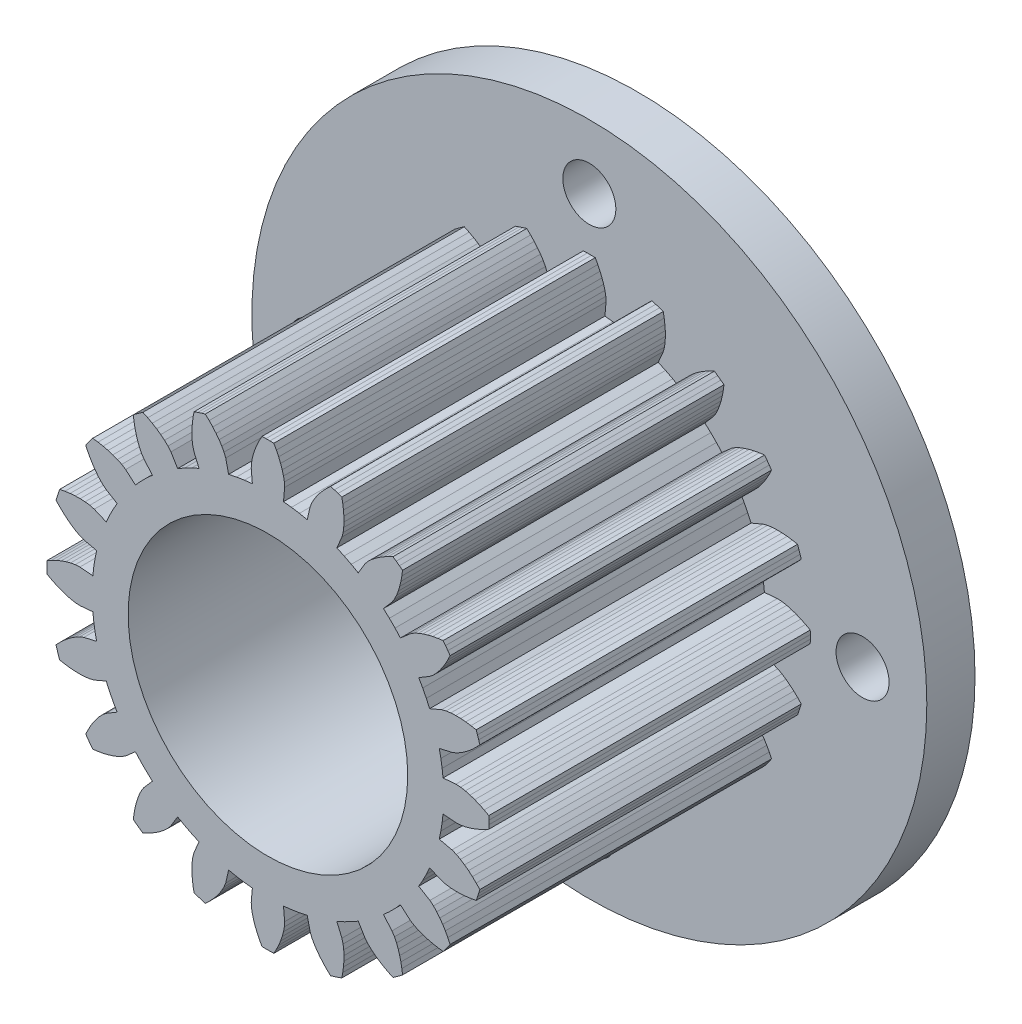
SolidWorks part; units mm, degrees
ref_plane "Спереди" through (0, 0, 0) normal (0, 0, 1) x (1, 0, 0)
ref_plane "Сверху" through (0, 0, 0) normal (0, 1, 0) x (1, 0, 0)
ref_plane "Справа" through (0, 0, 0) normal (1, 0, 0) x (0, 0, -1)
sketch "Эскиз1" plane through (0, 0, 0) normal (0, 0, 1) x (1, 0, 0)
  line L0 (10.8946, -0.9683) -> (11.7, -1.0399)
  line L1 (11.7, -1.0399) -> (11.9889, -1.0227)
  line L2 (11.9889, -1.0227) -> (12.2805, -0.9687)
  line L3 (12.2805, -0.9687) -> (12.5736, -0.889)
  line L4 (12.5736, -0.889) -> (12.8671, -0.7875)
  line L5 (12.8671, -0.7875) -> (13.1606, -0.6661)
  line L6 (13.1606, -0.6661) -> (13.4535, -0.5261)
  line L7 (13.4535, -0.5261) -> (13.7451, -0.3683)
  line L8 (13.7451, -0.3683) -> (13.7495, -0.1228)
  line L9 (13.7495, -0.1228) -> (13.7495, 0.1228)
  line L10 (13.7495, 0.1228) -> (13.7451, 0.3683)
  line L11 (13.7451, 0.3683) -> (13.4535, 0.5261)
  line L12 (13.4535, 0.5261) -> (13.1606, 0.6661)
  line L13 (13.1606, 0.6661) -> (12.8671, 0.7875)
  line L14 (12.8671, 0.7875) -> (12.5736, 0.889)
  line L15 (12.5736, 0.889) -> (12.2805, 0.9687)
  line L16 (12.2805, 0.9687) -> (11.9889, 1.0227)
  line L17 (11.9889, 1.0227) -> (11.7, 1.0399)
  line L18 (11.7, 1.0399) -> (10.8946, 0.9683)
  line L19 (10.8946, 0.9683) -> (10.8391, 1.4641)
  line L20 (10.8391, 1.4641) -> (10.761, 1.957)
  line L21 (10.761, 1.957) -> (10.6606, 2.4457)
  line L22 (10.6606, 2.4457) -> (11.4487, 2.6265)
  line L23 (11.4487, 2.6265) -> (11.7181, 2.7321)
  line L24 (11.7181, 2.7321) -> (11.9788, 2.8737)
  line L25 (11.9788, 2.8737) -> (12.2329, 3.0399)
  line L26 (12.2329, 3.0399) -> (12.4807, 3.2272)
  line L27 (12.4807, 3.2272) -> (12.7223, 3.4333)
  line L28 (12.7223, 3.4333) -> (12.9576, 3.657)
  line L29 (12.9576, 3.657) -> (13.1861, 3.8972)
  line L30 (13.1861, 3.8972) -> (13.1144, 4.1321)
  line L31 (13.1144, 4.1321) -> (13.0386, 4.3656)
  line L32 (13.0386, 4.3656) -> (12.9585, 4.5977)
  line L33 (12.9585, 4.5977) -> (12.6324, 4.6577)
  line L34 (12.6324, 4.6577) -> (12.3107, 4.7004)
  line L35 (12.3107, 4.7004) -> (11.994, 4.7252)
  line L36 (11.994, 4.7252) -> (11.6834, 4.731)
  line L37 (11.6834, 4.731) -> (11.3802, 4.7161)
  line L38 (11.3802, 4.7161) -> (11.0861, 4.6774)
  line L39 (11.0861, 4.6774) -> (10.8061, 4.6045)
  line L40 (10.8061, 4.6045) -> (10.0621, 4.2875)
  line L41 (10.0621, 4.2875) -> (9.8561, 4.7419)
  line L42 (9.8561, 4.7419) -> (9.6296, 5.1865)
  line L43 (9.6296, 5.1865) -> (9.383, 5.6203)
  line L44 (9.383, 5.6203) -> (10.0767, 6.0358)
  line L45 (10.0767, 6.0358) -> (10.3003, 6.2195)
  line L46 (10.3003, 6.2195) -> (10.5045, 6.4347)
  line L47 (10.5045, 6.4347) -> (10.6948, 6.6713)
  line L48 (10.6948, 6.6713) -> (10.8726, 6.926)
  line L49 (10.8726, 6.926) -> (11.0387, 7.1967)
  line L50 (11.0387, 7.1967) -> (11.1933, 7.4821)
  line L51 (11.1933, 7.4821) -> (11.3364, 7.7812)
  line L52 (11.3364, 7.7812) -> (11.1957, 7.9824)
  line L53 (11.1957, 7.9824) -> (11.0514, 8.181)
  line L54 (11.0514, 8.181) -> (10.9035, 8.3771)
  line L55 (10.9035, 8.3771) -> (10.5749, 8.3333)
  line L56 (10.5749, 8.3333) -> (10.2556, 8.2745)
  line L57 (10.2556, 8.2745) -> (9.9468, 8.2002)
  line L58 (9.9468, 8.2002) -> (9.6497, 8.1098)
  line L59 (9.6497, 8.1098) -> (9.3658, 8.002)
  line L60 (9.3658, 8.002) -> (9.0981, 7.8742)
  line L61 (9.0981, 7.8742) -> (8.8543, 7.7184)
  line L62 (8.8543, 7.7184) -> (8.2447, 7.187)
  line L63 (8.2447, 7.187) -> (7.9084, 7.5556)
  line L64 (7.9084, 7.5556) -> (7.5556, 7.9084)
  line L65 (7.5556, 7.9084) -> (7.187, 8.2447)
  line L66 (7.187, 8.2447) -> (7.7184, 8.8543)
  line L67 (7.7184, 8.8543) -> (7.8742, 9.0981)
  line L68 (7.8742, 9.0981) -> (8.002, 9.3658)
  line L69 (8.002, 9.3658) -> (8.1098, 9.6497)
  line L70 (8.1098, 9.6497) -> (8.2002, 9.9468)
  line L71 (8.2002, 9.9468) -> (8.2745, 10.2556)
  line L72 (8.2745, 10.2556) -> (8.3333, 10.5749)
  line L73 (8.3333, 10.5749) -> (8.3771, 10.9035)
  line L74 (8.3771, 10.9035) -> (8.181, 11.0514)
  line L75 (8.181, 11.0514) -> (7.9824, 11.1957)
  line L76 (7.9824, 11.1957) -> (7.7812, 11.3364)
  line L77 (7.7812, 11.3364) -> (7.4821, 11.1933)
  line L78 (7.4821, 11.1933) -> (7.1967, 11.0387)
  line L79 (7.1967, 11.0387) -> (6.926, 10.8726)
  line L80 (6.926, 10.8726) -> (6.6713, 10.6948)
  line L81 (6.6713, 10.6948) -> (6.4347, 10.5045)
  line L82 (6.4347, 10.5045) -> (6.2195, 10.3003)
  line L83 (6.2195, 10.3003) -> (6.0358, 10.0767)
  line L84 (6.0358, 10.0767) -> (5.6203, 9.383)
  line L85 (5.6203, 9.383) -> (5.1865, 9.6296)
  line L86 (5.1865, 9.6296) -> (4.7419, 9.8561)
  line L87 (4.7419, 9.8561) -> (4.2875, 10.0621)
  line L88 (4.2875, 10.0621) -> (4.6045, 10.8061)
  line L89 (4.6045, 10.8061) -> (4.6774, 11.0861)
  line L90 (4.6774, 11.0861) -> (4.7161, 11.3802)
  line L91 (4.7161, 11.3802) -> (4.731, 11.6834)
  line L92 (4.731, 11.6834) -> (4.7252, 11.994)
  line L93 (4.7252, 11.994) -> (4.7004, 12.3107)
  line L94 (4.7004, 12.3107) -> (4.6577, 12.6324)
  line L95 (4.6577, 12.6324) -> (4.5977, 12.9585)
  line L96 (4.5977, 12.9585) -> (4.3656, 13.0386)
  line L97 (4.3656, 13.0386) -> (4.1321, 13.1144)
  line L98 (4.1321, 13.1144) -> (3.8972, 13.1861)
  line L99 (3.8972, 13.1861) -> (3.657, 12.9576)
  line L100 (3.657, 12.9576) -> (3.4333, 12.7223)
  line L101 (3.4333, 12.7223) -> (3.2272, 12.4807)
  line L102 (3.2272, 12.4807) -> (3.0399, 12.2329)
  line L103 (3.0399, 12.2329) -> (2.8737, 11.9788)
  line L104 (2.8737, 11.9788) -> (2.7321, 11.7181)
  line L105 (2.7321, 11.7181) -> (2.6265, 11.4487)
  line L106 (2.6265, 11.4487) -> (2.4457, 10.6606)
  line L107 (2.4457, 10.6606) -> (1.957, 10.761)
  line L108 (1.957, 10.761) -> (1.4641, 10.8391)
  line L109 (1.4641, 10.8391) -> (0.9683, 10.8946)
  line L110 (0.9683, 10.8946) -> (1.0399, 11.7)
  line L111 (1.0399, 11.7) -> (1.0227, 11.9889)
  line L112 (1.0227, 11.9889) -> (0.9687, 12.2805)
  line L113 (0.9687, 12.2805) -> (0.889, 12.5736)
  line L114 (0.889, 12.5736) -> (0.7875, 12.8671)
  line L115 (0.7875, 12.8671) -> (0.6661, 13.1606)
  line L116 (0.6661, 13.1606) -> (0.5261, 13.4535)
  line L117 (0.5261, 13.4535) -> (0.3683, 13.7451)
  line L118 (0.3683, 13.7451) -> (0.1228, 13.7495)
  line L119 (0.1228, 13.7495) -> (-0.1228, 13.7495)
  line L120 (-0.1228, 13.7495) -> (-0.3683, 13.7451)
  line L121 (-0.3683, 13.7451) -> (-0.5261, 13.4535)
  line L122 (-0.5261, 13.4535) -> (-0.6661, 13.1606)
  line L123 (-0.6661, 13.1606) -> (-0.7875, 12.8671)
  line L124 (-0.7875, 12.8671) -> (-0.889, 12.5736)
  line L125 (-0.889, 12.5736) -> (-0.9687, 12.2805)
  line L126 (-0.9687, 12.2805) -> (-1.0227, 11.9889)
  line L127 (-1.0227, 11.9889) -> (-1.0399, 11.7)
  line L128 (-1.0399, 11.7) -> (-0.9683, 10.8946)
  line L129 (-0.9683, 10.8946) -> (-1.4641, 10.8391)
  line L130 (-1.4641, 10.8391) -> (-1.957, 10.761)
  line L131 (-1.957, 10.761) -> (-2.4457, 10.6606)
  line L132 (-2.4457, 10.6606) -> (-2.6265, 11.4487)
  line L133 (-2.6265, 11.4487) -> (-2.7321, 11.7181)
  line L134 (-2.7321, 11.7181) -> (-2.8737, 11.9788)
  line L135 (-2.8737, 11.9788) -> (-3.0399, 12.2329)
  line L136 (-3.0399, 12.2329) -> (-3.2272, 12.4807)
  line L137 (-3.2272, 12.4807) -> (-3.4333, 12.7223)
  line L138 (-3.4333, 12.7223) -> (-3.657, 12.9576)
  line L139 (-3.657, 12.9576) -> (-3.8972, 13.1861)
  line L140 (-3.8972, 13.1861) -> (-4.1321, 13.1144)
  line L141 (-4.1321, 13.1144) -> (-4.3656, 13.0386)
  line L142 (-4.3656, 13.0386) -> (-4.5977, 12.9585)
  line L143 (-4.5977, 12.9585) -> (-4.6577, 12.6324)
  line L144 (-4.6577, 12.6324) -> (-4.7004, 12.3107)
  line L145 (-4.7004, 12.3107) -> (-4.7252, 11.994)
  line L146 (-4.7252, 11.994) -> (-4.731, 11.6834)
  line L147 (-4.731, 11.6834) -> (-4.7161, 11.3802)
  line L148 (-4.7161, 11.3802) -> (-4.6774, 11.0861)
  line L149 (-4.6774, 11.0861) -> (-4.6045, 10.8061)
  line L150 (-4.6045, 10.8061) -> (-4.2875, 10.0621)
  line L151 (-4.2875, 10.0621) -> (-4.7419, 9.8561)
  line L152 (-4.7419, 9.8561) -> (-5.1865, 9.6296)
  line L153 (-5.1865, 9.6296) -> (-5.6203, 9.383)
  line L154 (-5.6203, 9.383) -> (-6.0358, 10.0767)
  line L155 (-6.0358, 10.0767) -> (-6.2195, 10.3003)
  line L156 (-6.2195, 10.3003) -> (-6.4347, 10.5045)
  line L157 (-6.4347, 10.5045) -> (-6.6713, 10.6948)
  line L158 (-6.6713, 10.6948) -> (-6.926, 10.8726)
  line L159 (-6.926, 10.8726) -> (-7.1967, 11.0387)
  line L160 (-7.1967, 11.0387) -> (-7.4821, 11.1933)
  line L161 (-7.4821, 11.1933) -> (-7.7812, 11.3364)
  line L162 (-7.7812, 11.3364) -> (-7.9824, 11.1957)
  line L163 (-7.9824, 11.1957) -> (-8.181, 11.0514)
  line L164 (-8.181, 11.0514) -> (-8.3771, 10.9035)
  line L165 (-8.3771, 10.9035) -> (-8.3333, 10.5749)
  line L166 (-8.3333, 10.5749) -> (-8.2745, 10.2556)
  line L167 (-8.2745, 10.2556) -> (-8.2002, 9.9468)
  line L168 (-8.2002, 9.9468) -> (-8.1098, 9.6497)
  line L169 (-8.1098, 9.6497) -> (-8.002, 9.3658)
  line L170 (-8.002, 9.3658) -> (-7.8742, 9.0981)
  line L171 (-7.8742, 9.0981) -> (-7.7184, 8.8543)
  line L172 (-7.7184, 8.8543) -> (-7.187, 8.2447)
  line L173 (-7.187, 8.2447) -> (-7.5556, 7.9084)
  line L174 (-7.5556, 7.9084) -> (-7.9084, 7.5556)
  line L175 (-7.9084, 7.5556) -> (-8.2447, 7.187)
  line L176 (-8.2447, 7.187) -> (-8.8543, 7.7184)
  line L177 (-8.8543, 7.7184) -> (-9.0981, 7.8742)
  line L178 (-9.0981, 7.8742) -> (-9.3658, 8.002)
  line L179 (-9.3658, 8.002) -> (-9.6497, 8.1098)
  line L180 (-9.6497, 8.1098) -> (-9.9468, 8.2002)
  line L181 (-9.9468, 8.2002) -> (-10.2556, 8.2745)
  line L182 (-10.2556, 8.2745) -> (-10.5749, 8.3333)
  line L183 (-10.5749, 8.3333) -> (-10.9035, 8.3771)
  line L184 (-10.9035, 8.3771) -> (-11.0514, 8.181)
  line L185 (-11.0514, 8.181) -> (-11.1957, 7.9824)
  line L186 (-11.1957, 7.9824) -> (-11.3364, 7.7812)
  line L187 (-11.3364, 7.7812) -> (-11.1933, 7.4821)
  line L188 (-11.1933, 7.4821) -> (-11.0387, 7.1967)
  line L189 (-11.0387, 7.1967) -> (-10.8726, 6.926)
  line L190 (-10.8726, 6.926) -> (-10.6948, 6.6713)
  line L191 (-10.6948, 6.6713) -> (-10.5045, 6.4347)
  line L192 (-10.5045, 6.4347) -> (-10.3003, 6.2195)
  line L193 (-10.3003, 6.2195) -> (-10.0767, 6.0358)
  line L194 (-10.0767, 6.0358) -> (-9.383, 5.6203)
  line L195 (-9.383, 5.6203) -> (-9.6296, 5.1865)
  line L196 (-9.6296, 5.1865) -> (-9.8561, 4.7419)
  line L197 (-9.8561, 4.7419) -> (-10.0621, 4.2875)
  line L198 (-10.0621, 4.2875) -> (-10.8061, 4.6045)
  line L199 (-10.8061, 4.6045) -> (-11.0861, 4.6774)
  line L200 (-11.0861, 4.6774) -> (-11.3802, 4.7161)
  line L201 (-11.3802, 4.7161) -> (-11.6834, 4.731)
  line L202 (-11.6834, 4.731) -> (-11.994, 4.7252)
  line L203 (-11.994, 4.7252) -> (-12.3107, 4.7004)
  line L204 (-12.3107, 4.7004) -> (-12.6324, 4.6577)
  line L205 (-12.6324, 4.6577) -> (-12.9585, 4.5977)
  line L206 (-12.9585, 4.5977) -> (-13.0386, 4.3656)
  line L207 (-13.0386, 4.3656) -> (-13.1144, 4.1321)
  line L208 (-13.1144, 4.1321) -> (-13.1861, 3.8972)
  line L209 (-13.1861, 3.8972) -> (-12.9576, 3.657)
  line L210 (-12.9576, 3.657) -> (-12.7223, 3.4333)
  line L211 (-12.7223, 3.4333) -> (-12.4807, 3.2272)
  line L212 (-12.4807, 3.2272) -> (-12.2329, 3.0399)
  line L213 (-12.2329, 3.0399) -> (-11.9788, 2.8737)
  line L214 (-11.9788, 2.8737) -> (-11.7181, 2.7321)
  line L215 (-11.7181, 2.7321) -> (-11.4487, 2.6265)
  line L216 (-11.4487, 2.6265) -> (-10.6606, 2.4457)
  line L217 (-10.6606, 2.4457) -> (-10.761, 1.957)
  line L218 (-10.761, 1.957) -> (-10.8391, 1.4641)
  line L219 (-10.8391, 1.4641) -> (-10.8946, 0.9683)
  line L220 (-10.8946, 0.9683) -> (-11.7, 1.0399)
  line L221 (-11.7, 1.0399) -> (-11.9889, 1.0227)
  line L222 (-11.9889, 1.0227) -> (-12.2805, 0.9687)
  line L223 (-12.2805, 0.9687) -> (-12.5736, 0.889)
  line L224 (-12.5736, 0.889) -> (-12.8671, 0.7875)
  line L225 (-12.8671, 0.7875) -> (-13.1606, 0.6661)
  line L226 (-13.1606, 0.6661) -> (-13.4535, 0.5261)
  line L227 (-13.4535, 0.5261) -> (-13.7451, 0.3683)
  line L228 (-13.7451, 0.3683) -> (-13.7495, 0.1228)
  line L229 (-13.7495, 0.1228) -> (-13.7495, -0.1228)
  line L230 (-13.7495, -0.1228) -> (-13.7451, -0.3683)
  line L231 (-13.7451, -0.3683) -> (-13.4535, -0.5261)
  line L232 (-13.4535, -0.5261) -> (-13.1606, -0.6661)
  line L233 (-13.1606, -0.6661) -> (-12.8671, -0.7875)
  line L234 (-12.8671, -0.7875) -> (-12.5736, -0.889)
  line L235 (-12.5736, -0.889) -> (-12.2805, -0.9687)
  line L236 (-12.2805, -0.9687) -> (-11.9889, -1.0227)
  line L237 (-11.9889, -1.0227) -> (-11.7, -1.0399)
  line L238 (-11.7, -1.0399) -> (-10.8946, -0.9683)
  line L239 (-10.8946, -0.9683) -> (-10.8391, -1.4641)
  line L240 (-10.8391, -1.4641) -> (-10.761, -1.957)
  line L241 (-10.761, -1.957) -> (-10.6606, -2.4457)
  line L242 (-10.6606, -2.4457) -> (-11.4487, -2.6265)
  line L243 (-11.4487, -2.6265) -> (-11.7181, -2.7321)
  line L244 (-11.7181, -2.7321) -> (-11.9788, -2.8737)
  line L245 (-11.9788, -2.8737) -> (-12.2329, -3.0399)
  line L246 (-12.2329, -3.0399) -> (-12.4807, -3.2272)
  line L247 (-12.4807, -3.2272) -> (-12.7223, -3.4333)
  line L248 (-12.7223, -3.4333) -> (-12.9576, -3.657)
  line L249 (-12.9576, -3.657) -> (-13.1861, -3.8972)
  line L250 (-13.1861, -3.8972) -> (-13.1144, -4.1321)
  line L251 (-13.1144, -4.1321) -> (-13.0386, -4.3656)
  line L252 (-13.0386, -4.3656) -> (-12.9585, -4.5977)
  line L253 (-12.9585, -4.5977) -> (-12.6324, -4.6577)
  line L254 (-12.6324, -4.6577) -> (-12.3107, -4.7004)
  line L255 (-12.3107, -4.7004) -> (-11.994, -4.7252)
  line L256 (-11.994, -4.7252) -> (-11.6834, -4.731)
  line L257 (-11.6834, -4.731) -> (-11.3802, -4.7161)
  line L258 (-11.3802, -4.7161) -> (-11.0861, -4.6774)
  line L259 (-11.0861, -4.6774) -> (-10.8061, -4.6045)
  line L260 (-10.8061, -4.6045) -> (-10.0621, -4.2875)
  line L261 (-10.0621, -4.2875) -> (-9.8561, -4.7419)
  line L262 (-9.8561, -4.7419) -> (-9.6296, -5.1865)
  line L263 (-9.6296, -5.1865) -> (-9.383, -5.6203)
  line L264 (-9.383, -5.6203) -> (-10.0767, -6.0358)
  line L265 (-10.0767, -6.0358) -> (-10.3003, -6.2195)
  line L266 (-10.3003, -6.2195) -> (-10.5045, -6.4347)
  line L267 (-10.5045, -6.4347) -> (-10.6948, -6.6713)
  line L268 (-10.6948, -6.6713) -> (-10.8726, -6.926)
  line L269 (-10.8726, -6.926) -> (-11.0387, -7.1967)
  line L270 (-11.0387, -7.1967) -> (-11.1933, -7.4821)
  line L271 (-11.1933, -7.4821) -> (-11.3364, -7.7812)
  line L272 (-11.3364, -7.7812) -> (-11.1957, -7.9824)
  line L273 (-11.1957, -7.9824) -> (-11.0514, -8.181)
  line L274 (-11.0514, -8.181) -> (-10.9035, -8.3771)
  line L275 (-10.9035, -8.3771) -> (-10.5749, -8.3333)
  line L276 (-10.5749, -8.3333) -> (-10.2556, -8.2745)
  line L277 (-10.2556, -8.2745) -> (-9.9468, -8.2002)
  line L278 (-9.9468, -8.2002) -> (-9.6497, -8.1098)
  line L279 (-9.6497, -8.1098) -> (-9.3658, -8.002)
  line L280 (-9.3658, -8.002) -> (-9.0981, -7.8742)
  line L281 (-9.0981, -7.8742) -> (-8.8543, -7.7184)
  line L282 (-8.8543, -7.7184) -> (-8.2447, -7.187)
  line L283 (-8.2447, -7.187) -> (-7.9084, -7.5556)
  line L284 (-7.9084, -7.5556) -> (-7.5556, -7.9084)
  line L285 (-7.5556, -7.9084) -> (-7.187, -8.2447)
  line L286 (-7.187, -8.2447) -> (-7.7184, -8.8543)
  line L287 (-7.7184, -8.8543) -> (-7.8742, -9.0981)
  line L288 (-7.8742, -9.0981) -> (-8.002, -9.3658)
  line L289 (-8.002, -9.3658) -> (-8.1098, -9.6497)
  line L290 (-8.1098, -9.6497) -> (-8.2002, -9.9468)
  line L291 (-8.2002, -9.9468) -> (-8.2745, -10.2556)
  line L292 (-8.2745, -10.2556) -> (-8.3333, -10.5749)
  line L293 (-8.3333, -10.5749) -> (-8.3771, -10.9035)
  line L294 (-8.3771, -10.9035) -> (-8.181, -11.0514)
  line L295 (-8.181, -11.0514) -> (-7.9824, -11.1957)
  line L296 (-7.9824, -11.1957) -> (-7.7812, -11.3364)
  line L297 (-7.7812, -11.3364) -> (-7.4821, -11.1933)
  line L298 (-7.4821, -11.1933) -> (-7.1967, -11.0387)
  line L299 (-7.1967, -11.0387) -> (-6.926, -10.8726)
  line L300 (-6.926, -10.8726) -> (-6.6713, -10.6948)
  line L301 (-6.6713, -10.6948) -> (-6.4347, -10.5045)
  line L302 (-6.4347, -10.5045) -> (-6.2195, -10.3003)
  line L303 (-6.2195, -10.3003) -> (-6.0358, -10.0767)
  line L304 (-6.0358, -10.0767) -> (-5.6203, -9.383)
  line L305 (-5.6203, -9.383) -> (-5.1865, -9.6296)
  line L306 (-5.1865, -9.6296) -> (-4.7419, -9.8561)
  line L307 (-4.7419, -9.8561) -> (-4.2875, -10.0621)
  line L308 (-4.2875, -10.0621) -> (-4.6045, -10.8061)
  line L309 (-4.6045, -10.8061) -> (-4.6774, -11.0861)
  line L310 (-4.6774, -11.0861) -> (-4.7161, -11.3802)
  line L311 (-4.7161, -11.3802) -> (-4.731, -11.6834)
  line L312 (-4.731, -11.6834) -> (-4.7252, -11.994)
  line L313 (-4.7252, -11.994) -> (-4.7004, -12.3107)
  line L314 (-4.7004, -12.3107) -> (-4.6577, -12.6324)
  line L315 (-4.6577, -12.6324) -> (-4.5977, -12.9585)
  line L316 (-4.5977, -12.9585) -> (-4.3656, -13.0386)
  line L317 (-4.3656, -13.0386) -> (-4.1321, -13.1144)
  line L318 (-4.1321, -13.1144) -> (-3.8972, -13.1861)
  line L319 (-3.8972, -13.1861) -> (-3.657, -12.9576)
  line L320 (-3.657, -12.9576) -> (-3.4333, -12.7223)
  line L321 (-3.4333, -12.7223) -> (-3.2272, -12.4807)
  line L322 (-3.2272, -12.4807) -> (-3.0399, -12.2329)
  line L323 (-3.0399, -12.2329) -> (-2.8737, -11.9788)
  line L324 (-2.8737, -11.9788) -> (-2.7321, -11.7181)
  line L325 (-2.7321, -11.7181) -> (-2.6265, -11.4487)
  line L326 (-2.6265, -11.4487) -> (-2.4457, -10.6606)
  line L327 (-2.4457, -10.6606) -> (-1.957, -10.761)
  line L328 (-1.957, -10.761) -> (-1.4641, -10.8391)
  line L329 (-1.4641, -10.8391) -> (-0.9683, -10.8946)
  line L330 (-0.9683, -10.8946) -> (-1.0399, -11.7)
  line L331 (-1.0399, -11.7) -> (-1.0227, -11.9889)
  line L332 (-1.0227, -11.9889) -> (-0.9687, -12.2805)
  line L333 (-0.9687, -12.2805) -> (-0.889, -12.5736)
  line L334 (-0.889, -12.5736) -> (-0.7875, -12.8671)
  line L335 (-0.7875, -12.8671) -> (-0.6661, -13.1606)
  line L336 (-0.6661, -13.1606) -> (-0.5261, -13.4535)
  line L337 (-0.5261, -13.4535) -> (-0.3683, -13.7451)
  line L338 (-0.3683, -13.7451) -> (-0.1228, -13.7495)
  line L339 (-0.1228, -13.7495) -> (0.1228, -13.7495)
  line L340 (0.1228, -13.7495) -> (0.3683, -13.7451)
  line L341 (0.3683, -13.7451) -> (0.5261, -13.4535)
  line L342 (0.5261, -13.4535) -> (0.6661, -13.1606)
  line L343 (0.6661, -13.1606) -> (0.7875, -12.8671)
  line L344 (0.7875, -12.8671) -> (0.889, -12.5736)
  line L345 (0.889, -12.5736) -> (0.9687, -12.2805)
  line L346 (0.9687, -12.2805) -> (1.0227, -11.9889)
  line L347 (1.0227, -11.9889) -> (1.0399, -11.7)
  line L348 (1.0399, -11.7) -> (0.9683, -10.8946)
  line L349 (0.9683, -10.8946) -> (1.4641, -10.8391)
  line L350 (1.4641, -10.8391) -> (1.957, -10.761)
  line L351 (1.957, -10.761) -> (2.4457, -10.6606)
  line L352 (2.4457, -10.6606) -> (2.6265, -11.4487)
  line L353 (2.6265, -11.4487) -> (2.7321, -11.7181)
  line L354 (2.7321, -11.7181) -> (2.8737, -11.9788)
  line L355 (2.8737, -11.9788) -> (3.0399, -12.2329)
  line L356 (3.0399, -12.2329) -> (3.2272, -12.4807)
  line L357 (3.2272, -12.4807) -> (3.4333, -12.7223)
  line L358 (3.4333, -12.7223) -> (3.657, -12.9576)
  line L359 (3.657, -12.9576) -> (3.8972, -13.1861)
  line L360 (3.8972, -13.1861) -> (4.1321, -13.1144)
  line L361 (4.1321, -13.1144) -> (4.3656, -13.0386)
  line L362 (4.3656, -13.0386) -> (4.5977, -12.9585)
  line L363 (4.5977, -12.9585) -> (4.6577, -12.6324)
  line L364 (4.6577, -12.6324) -> (4.7004, -12.3107)
  line L365 (4.7004, -12.3107) -> (4.7252, -11.994)
  line L366 (4.7252, -11.994) -> (4.731, -11.6834)
  line L367 (4.731, -11.6834) -> (4.7161, -11.3802)
  line L368 (4.7161, -11.3802) -> (4.6774, -11.0861)
  line L369 (4.6774, -11.0861) -> (4.6045, -10.8061)
  line L370 (4.6045, -10.8061) -> (4.2875, -10.0621)
  line L371 (4.2875, -10.0621) -> (4.7419, -9.8561)
  line L372 (4.7419, -9.8561) -> (5.1865, -9.6296)
  line L373 (5.1865, -9.6296) -> (5.6203, -9.383)
  line L374 (5.6203, -9.383) -> (6.0358, -10.0767)
  line L375 (6.0358, -10.0767) -> (6.2195, -10.3003)
  line L376 (6.2195, -10.3003) -> (6.4347, -10.5045)
  line L377 (6.4347, -10.5045) -> (6.6713, -10.6948)
  line L378 (6.6713, -10.6948) -> (6.926, -10.8726)
  line L379 (6.926, -10.8726) -> (7.1967, -11.0387)
  line L380 (7.1967, -11.0387) -> (7.4821, -11.1933)
  line L381 (7.4821, -11.1933) -> (7.7812, -11.3364)
  line L382 (7.7812, -11.3364) -> (7.9824, -11.1957)
  line L383 (7.9824, -11.1957) -> (8.181, -11.0514)
  line L384 (8.181, -11.0514) -> (8.3771, -10.9035)
  line L385 (8.3771, -10.9035) -> (8.3333, -10.5749)
  line L386 (8.3333, -10.5749) -> (8.2745, -10.2556)
  line L387 (8.2745, -10.2556) -> (8.2002, -9.9468)
  line L388 (8.2002, -9.9468) -> (8.1098, -9.6497)
  line L389 (8.1098, -9.6497) -> (8.002, -9.3658)
  line L390 (8.002, -9.3658) -> (7.8742, -9.0981)
  line L391 (7.8742, -9.0981) -> (7.7184, -8.8543)
  line L392 (7.7184, -8.8543) -> (7.187, -8.2447)
  line L393 (7.187, -8.2447) -> (7.5556, -7.9084)
  line L394 (7.5556, -7.9084) -> (7.9084, -7.5556)
  line L395 (7.9084, -7.5556) -> (8.2447, -7.187)
  line L396 (8.2447, -7.187) -> (8.8543, -7.7184)
  line L397 (8.8543, -7.7184) -> (9.0981, -7.8742)
  line L398 (9.0981, -7.8742) -> (9.3658, -8.002)
  line L399 (9.3658, -8.002) -> (9.6497, -8.1098)
  line L400 (9.6497, -8.1098) -> (9.9468, -8.2002)
  line L401 (9.9468, -8.2002) -> (10.2556, -8.2745)
  line L402 (10.2556, -8.2745) -> (10.5749, -8.3333)
  line L403 (10.5749, -8.3333) -> (10.9035, -8.3771)
  line L404 (10.9035, -8.3771) -> (11.0514, -8.181)
  line L405 (11.0514, -8.181) -> (11.1957, -7.9824)
  line L406 (11.1957, -7.9824) -> (11.3364, -7.7812)
  line L407 (11.3364, -7.7812) -> (11.1933, -7.4821)
  line L408 (11.1933, -7.4821) -> (11.0387, -7.1967)
  line L409 (11.0387, -7.1967) -> (10.8726, -6.926)
  line L410 (10.8726, -6.926) -> (10.6948, -6.6713)
  line L411 (10.6948, -6.6713) -> (10.5045, -6.4347)
  line L412 (10.5045, -6.4347) -> (10.3003, -6.2195)
  line L413 (10.3003, -6.2195) -> (10.0767, -6.0358)
  line L414 (10.0767, -6.0358) -> (9.383, -5.6203)
  line L415 (9.383, -5.6203) -> (9.6296, -5.1865)
  line L416 (9.6296, -5.1865) -> (9.8561, -4.7419)
  line L417 (9.8561, -4.7419) -> (10.0621, -4.2875)
  line L418 (10.0621, -4.2875) -> (10.8061, -4.6045)
  line L419 (10.8061, -4.6045) -> (11.0861, -4.6774)
  line L420 (11.0861, -4.6774) -> (11.3802, -4.7161)
  line L421 (11.3802, -4.7161) -> (11.6834, -4.731)
  line L422 (11.6834, -4.731) -> (11.994, -4.7252)
  line L423 (11.994, -4.7252) -> (12.3107, -4.7004)
  line L424 (12.3107, -4.7004) -> (12.6324, -4.6577)
  line L425 (12.6324, -4.6577) -> (12.9585, -4.5977)
  line L426 (12.9585, -4.5977) -> (13.0386, -4.3656)
  line L427 (13.0386, -4.3656) -> (13.1144, -4.1321)
  line L428 (13.1144, -4.1321) -> (13.1861, -3.8972)
  line L429 (13.1861, -3.8972) -> (12.9576, -3.657)
  line L430 (12.9576, -3.657) -> (12.7223, -3.4333)
  line L431 (12.7223, -3.4333) -> (12.4807, -3.2272)
  line L432 (12.4807, -3.2272) -> (12.2329, -3.0399)
  line L433 (12.2329, -3.0399) -> (11.9788, -2.8737)
  line L434 (11.9788, -2.8737) -> (11.7181, -2.7321)
  line L435 (11.7181, -2.7321) -> (11.4487, -2.6265)
  line L436 (11.4487, -2.6265) -> (10.6606, -2.4457)
  line L437 (10.6606, -2.4457) -> (10.761, -1.957)
  line L438 (10.761, -1.957) -> (10.8391, -1.4641)
  line L439 (10.8391, -1.4641) -> (10.8946, -0.9683)
  circle A0 centre (0, 0) radius 8.7
extrude "Sun_teeth" add sketch "Эскиз1" along normal blind 20 from offset 35
sketch "Эскиз2" plane through (0, 0, 0) normal (0, 0, 1) x (1, 0, 0)
  circle A0 centre (0, 0) radius 21
  circle A1 centre (0, 0) radius 8.7
extrude "Sun_flange" add sketch "Эскиз2" along normal blind 3 from offset 32
sketch "Эскиз3" plane through (0, 0, 0) normal (0, 0, 1) x (1, 0, 0)
  circle A0 centre (17, 0) radius 1.65
  circle A1 centre (0, 17) radius 1.65
  circle A2 centre (-17, 0) radius 1.65
  circle A3 centre (0, -17) radius 1.65
extrude "Through_holes" cut sketch "Эскиз3" against normal mid plane 200
